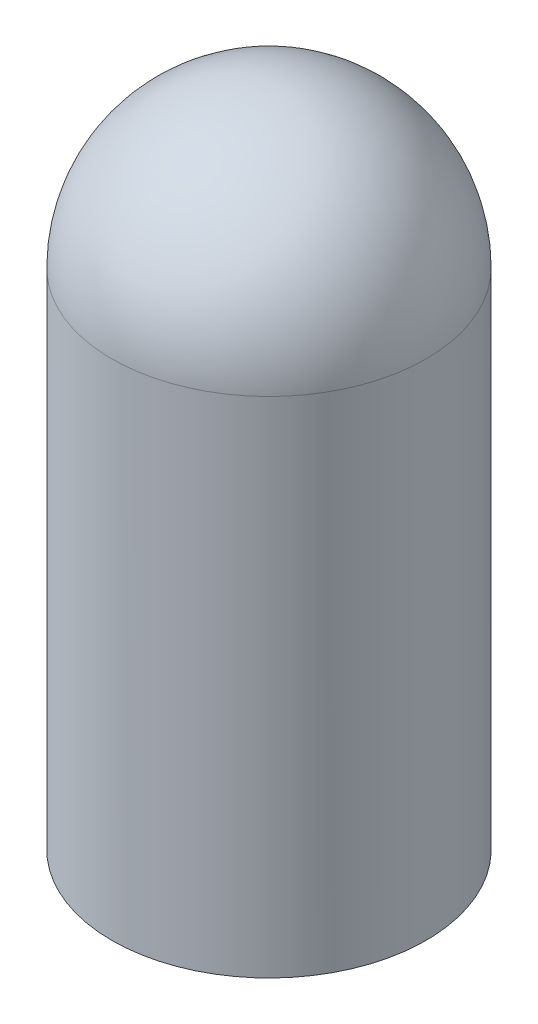
SolidWorks part; units mm, degrees
ref_plane "Front Plane" through (0, 0, 0) normal (0, 0, 1) x (1, 0, 0)
ref_plane "Top Plane" through (0, 0, 0) normal (0, 1, 0) x (1, 0, 0)
ref_plane "Right Plane" through (0, 0, 0) normal (1, 0, 0) x (0, 0, -1)
sketch "Sketch2" plane through (0, 0, 0) normal (0, 0, 1) x (1, 0, 0)
  line L0 (9.75, 0) -> (9.75, 31.25)
  line L1 (9.75, 31.25) -> (-16.698, 31.25) construction
  line L2 (9.75, 0) -> (0, 0)
  line L3 (0, 0) -> (0, 41)
  arc A0 (9.75, 31.25) -> (0, 41) centre (0, 31.25) ccw
  dimension "D1" = 31.25
  dimension "D2" = 9.75
revolve "Revolve1" add sketch "Sketch2" angle 360 about L3
shell "Shell1" thickness 0.5
